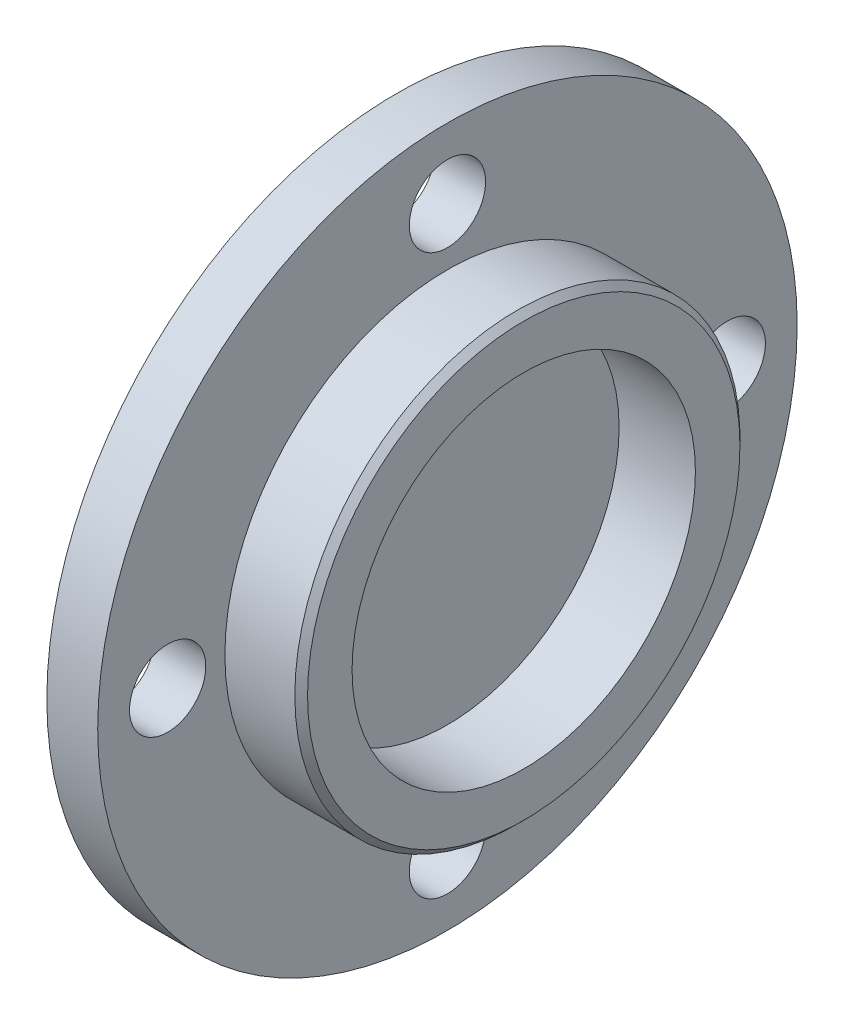
SolidWorks part; units mm, degrees
ref_plane "Front Plane" through (0, 0, 0) normal (0, 0, 1) x (1, 0, 0)
ref_plane "Top Plane" through (0, 0, 0) normal (0, 1, 0) x (1, 0, 0)
ref_plane "Right Plane" through (0, 0, 0) normal (1, 0, 0) x (0, 0, -1)
sketch "Sketch1" plane through (0, 0, 0) normal (0, 1, 0) x (1, 0, 0)
  line L0 (0, 0) -> (53.1893, 0) construction
  line L1 (0, 0) -> (0, 27.5)
  line L2 (0, 27.5) -> (4, 27.5)
  line L3 (4, 27.5) -> (4, 17.5)
  line L4 (4, 17.5) -> (10, 17.5)
  line L5 (10, 17.5) -> (10, 13.5)
  line L6 (10, 13.5) -> (4, 13.5)
  line L7 (4, 13.5) -> (4, 0)
  line L8 (0, 0) -> (4, 0)
  dimension "D1" = 27.5
  dimension "D2" = 13.5
  dimension "D3" = 17.5
  dimension "D4" = 4
  dimension "D5" = 10
revolve "Revolve2" add sketch "Sketch1" angle 360 about L0
chamfer "Chamfer1" distance 0.5 angle 45 1 edges at (10, 0, 17.5)
sketch "Sketch3" plane through (0, 0, 0) normal (-1, 0, 0) x (0, 0, 1)
  circle A0 centre (0, 0) radius 22 construction
  circle A1 centre (0, 22) radius 3
  circle A2 centre (22, 0) radius 3
  circle A3 centre (0, -22) radius 3
  circle A4 centre (-22, 0) radius 3
  point P14 (0, 0)
  dimension "D1" = 4
extrude "Cut-Extrude1" cut sketch "Sketch3" against normal through all
